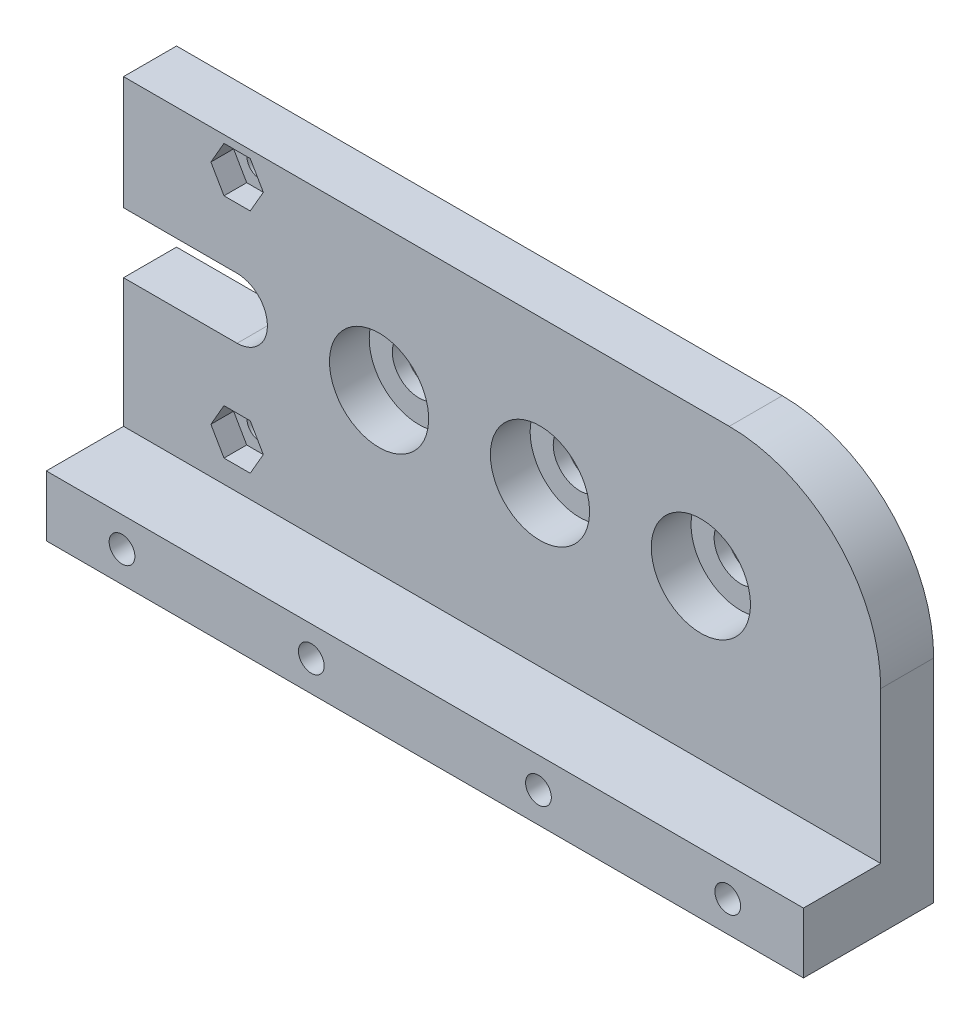
SolidWorks part; units mm, degrees
ref_plane "Front Plane" through (0, 0, 0) normal (0, 0, 1) x (1, 0, 0)
ref_plane "Top Plane" through (0, 0, 0) normal (0, 1, 0) x (1, 0, 0)
ref_plane "Right Plane" through (0, 0, 0) normal (1, 0, 0) x (0, 0, -1)
sketch "Sketch1" plane through (0, 0, 0) normal (0, 0, 1) x (1, 0, 0)
  line L1 (0, 0) -> (100, 0)
  line L2 (0, 0) -> (0, 48)
  line L3 (0, 48) -> (100, 48)
  line L4 (100, 0) -> (100, 48)
  dimension "D1" = 100
  dimension "D2" = 48
extrude "Boss-Extrude1" add sketch "Sketch1" along normal blind 7
sketch "Sketch2" plane through (0, 0, 7) normal (0, 0, 1) x (1, 0, 0)
  line L0 (0, 0) -> (100, 0) construction
  line L1 (0, 48) -> (0, 0) construction
  line L2 (15, 33) -> (0, 33)
  line L3 (15, 25) -> (0, 25)
  line L4 (0, 25) -> (0, 33)
  circle A0 centre (15, 29) radius 4
  circle A1 centre (33.75, 29) radius 3.5
  circle A2 centre (55, 29) radius 3.5
  circle A3 centre (76.25, 29) radius 3.5
  line M5 (0, 48) -> (0, 0)
  dimension "D1" = 7
  dimension "D2" = 18.75
  dimension "D3" = 21.25
  dimension "D4" = 21.25
  dimension "D5" = 29
  dimension "D6" = 15
  dimension "D7" = 8
extrude "Cut-Extrude1" cut sketch "Sketch2" against normal up to next contours A0 L2 L3 M5 | A0 | A1 | A2 | A3
sketch "Sketch3" plane through (0, 0, 0) normal (0, 0, -1) x (-1, 0, 0)
  line L0 (0, 48) -> (0, 33) construction
  line L1 (-100, 0) -> (0, 0)
  line L2 (-100, 0) -> (-100, 8)
  line L3 (-100, 8) -> (0, 8)
  line L4 (0, 0) -> (0, 8)
  dimension "D1" = 8
extrude "Boss-Extrude2" add sketch "Sketch3" along normal blind 10.2
sketch "Sketch4" plane through (0, 0, 0) normal (0, 0, -1) x (-1, 0, 0)
  circle A0 centre (-76.25, 29) radius 6.55
  circle A1 centre (-55, 29) radius 6.55
  circle A2 centre (-33.75, 29) radius 6.55
  dimension "D1" = 13.1
extrude "Cut-Extrude2" cut sketch "Sketch4" against normal blind 5.25
sketch "Sketch5" plane through (0, 0, 7) normal (0, 0, 1) x (1, 0, 0)
  line L0 (35, 4.0521) -> (65, 4) construction
  line L1 (0, 0) -> (100, 0) construction
  circle A0 centre (35, 4.0521) radius 2.6
  circle A1 centre (65, 4) radius 2.6
  point P6 (50, 0)
  point P7 (50, 4.0261)
  dimension "D1" = 5.2
  dimension "D2" = 30
  dimension "D3" = 4
extrude "Cut-Extrude3" cut sketch "Sketch5" against normal blind 7
sketch "Sketch7" plane through (0, 0, 0) normal (0, 0, 1) x (1, 0, 0)
  circle A0 centre (35, 4.0521) radius 1.7
  circle A1 centre (65, 4) radius 1.7
  dimension "D1" = 3.4
extrude "Cut-Extrude4" cut sketch "Sketch7" against normal through all
sketch "Sketch8" plane through (0, 0, 7) normal (0, 0, 1) x (1, 0, 0)
  line L0 (10, 4.0521) -> (35, 4.0521) construction
  line L1 (0, 48) -> (0, 33) construction
  line L2 (100, 0) -> (100, 48) construction
  circle A0 centre (10, 4.0521) radius 1.7
  circle A1 centre (90, 4.0521) radius 1.7
  dimension "D1" = 3.4
  dimension "D2" = 10
  dimension "D3" = 10
extrude "Cut-Extrude5" cut sketch "Sketch8" against normal up to next
mirror "Mirror1" about plane through (0, 0, -10.2) normal (0, 0, 1) of bodies 110
delete or keep bodies "Body-Delete/Keep 1" type delete bodies bodies 110
sketch "Sketch9" plane through (0, 0, -27.4) normal (0, 0, -1) x (-1, 0, 0)
  line L1 (-88.2679, 1.0521) -> (-86.5359, 4.0521)
  line L2 (-86.5359, 4.0521) -> (-88.2679, 7.0521)
  line L3 (-88.2679, 7.0521) -> (-91.7321, 7.0521)
  line L4 (-91.7321, 7.0521) -> (-93.4641, 4.0521)
  line L5 (-93.4641, 4.0521) -> (-91.7321, 1.0521)
  line L6 (-91.7321, 1.0521) -> (-88.2679, 1.0521)
  line L7 (-13.4641, 4.0521) -> (-11.7321, 1.0521)
  line L8 (-11.7321, 1.0521) -> (-8.2679, 1.0521)
  line L9 (-8.2679, 1.0521) -> (-6.5359, 4.0521)
  line L10 (-6.5359, 4.0521) -> (-8.2679, 7.0521)
  line L11 (-8.2679, 7.0521) -> (-11.7321, 7.0521)
  line L12 (-11.7321, 7.0521) -> (-13.4641, 4.0521)
  circle A0 centre (-90, 4.0521) radius 3 construction
  circle A1 centre (-10, 4.0521) radius 3 construction
  dimension "D1" = 6
extrude "Cut-Extrude6" cut sketch "Sketch9" against normal blind 3
sketch "Sketch10" plane through (0, 0, -27.4) normal (0, 0, -1) x (-1, 0, 0)
  line L0 (-15, 44) -> (-15, 29) construction
  circle A0 centre (-15, 44) radius 1.7
  circle A1 centre (-15, 14) radius 1.7
  dimension "D1" = 3.4
  dimension "D2" = 30
  dimension "D3" = 15
extrude "Cut-Extrude7" cut sketch "Sketch10" against normal up to next
sketch "Sketch11" plane through (0, 0, -20.4) normal (0, 0, 1) x (1, 0, 0)
  line L1 (18.4641, 44) -> (16.7321, 47)
  line L2 (16.7321, 47) -> (13.2679, 47)
  line L3 (13.2679, 47) -> (11.5359, 44)
  line L4 (11.5359, 44) -> (13.2679, 41)
  line L5 (13.2679, 41) -> (16.7321, 41)
  line L6 (16.7321, 41) -> (18.4641, 44)
  line L7 (18.4641, 14) -> (16.7321, 17)
  line L8 (16.7321, 17) -> (13.2679, 17)
  line L9 (13.2679, 17) -> (11.5359, 14)
  line L10 (11.5359, 14) -> (13.2679, 11)
  line L11 (13.2679, 11) -> (16.7321, 11)
  line L12 (16.7321, 11) -> (18.4641, 14)
  circle A0 centre (15, 44) radius 3 construction
  circle A1 centre (15, 14) radius 3 construction
  dimension "D1" = 6
extrude "Cut-Extrude8" cut sketch "Sketch11" against normal blind 3
fillet "Fillet1" radius 20 1 edges at (100, 48, -23.9)
